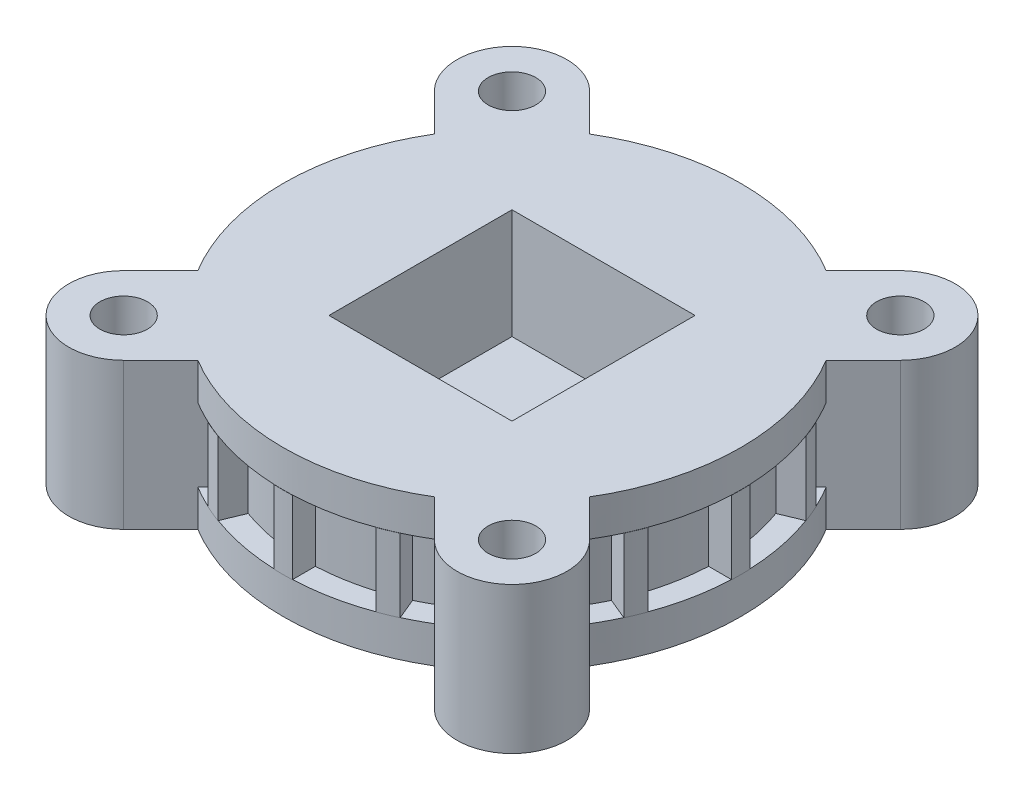
SolidWorks part; units mm, degrees
ref_plane "Front Plane" through (0, 0, 0) normal (0, 0, 1) x (1, 0, 0)
ref_plane "Top Plane" through (0, 0, 0) normal (0, 1, 0) x (1, 0, 0)
ref_plane "Right Plane" through (0, 0, 0) normal (1, 0, 0) x (0, 0, -1)
sketch "Sketch1" plane through (0, 0, 0) normal (0, 1, 0) x (1, 0, 0)
  line L1 (21.4036, 12.9184) -> (25.4558, 16.9706)
  line L2 (12.9184, 21.4036) -> (16.9706, 25.4558)
  line L6 (21.4036, -12.9184) -> (25.4558, -16.9706)
  line L7 (12.9184, -21.4036) -> (16.9706, -25.4558)
  line L8 (-12.9184, -21.4036) -> (-16.9706, -25.4558)
  line L9 (-21.4036, -12.9184) -> (-25.4558, -16.9706)
  line L10 (-21.4036, 12.9184) -> (-25.4558, 16.9706)
  line L11 (-12.9184, 21.4036) -> (-16.9706, 25.4558)
  arc A0 (-12.9184, -21.4036) -> (12.9184, -21.4036) centre (0, 0) ccw
  arc A2 (16.9706, -25.4558) -> (25.4558, -16.9706) centre (21.2132, -21.2132) ccw
  arc A3 (-25.4558, -16.9706) -> (-16.9706, -25.4558) centre (-21.2132, -21.2132) ccw
  arc A4 (-16.9706, 25.4558) -> (-25.4558, 16.9706) centre (-21.2132, 21.2132) ccw
  arc A5 (21.4036, -12.9184) -> (21.4036, 12.9184) centre (0, 0) ccw
  arc A6 (12.9184, 21.4036) -> (-12.9184, 21.4036) centre (0, 0) ccw
  arc A7 (25.4558, 16.9706) -> (16.9706, 25.4558) centre (21.2132, 21.2132) ccw
  arc A8 (-21.4036, 12.9184) -> (-21.4036, -12.9184) centre (0, 0) ccw
  point P14 (0, 0)
  point P35 (0, 0)
  dimension "D1" = 4
extrude "Boss-Extrude1" add sketch "Sketch1" along normal blind 4
ref_plane "Plane1" through (0, 4, 0) normal (0, 1, 0) x (1, 0, 0)
sketch "Sketch2" plane through (0, 4, 0) normal (0, 1, 0) x (1, 0, 0)
  line L0 (-1, 25) -> (-1, 22.4778)
  line L1 (19.5764, 11.0911) -> (25.4558, 16.9706)
  line L2 (11.0911, 19.5764) -> (16.9706, 25.4558)
  line L3 (8.6432, 23.4797) -> (7.678, 21.1494)
  line L4 (1, 25) -> (1, 22.4778)
  line L5 (10.491, 22.7143) -> (9.5257, 20.3841)
  line L6 (19.5764, -11.0911) -> (25.4558, -16.9706)
  line L7 (11.0911, -19.5764) -> (16.9706, -25.4558)
  line L8 (22.7143, 10.491) -> (20.3841, 9.5257)
  line L9 (23.4797, 8.6432) -> (21.1494, 7.678)
  line L10 (25, 1) -> (22.4778, 1)
  line L11 (25, -1) -> (22.4778, -1)
  line L12 (23.4797, -8.6432) -> (21.1494, -7.678)
  line L13 (22.7143, -10.491) -> (20.3841, -9.5257)
  line L16 (10.491, -22.7143) -> (9.5257, -20.3841)
  line L17 (8.6432, -23.4797) -> (7.678, -21.1494)
  line L18 (1, -25) -> (1, -22.4778)
  line L19 (-1, -25) -> (-1, -22.4778)
  line L20 (-8.6432, -23.4797) -> (-7.678, -21.1494)
  line L21 (-10.491, -22.7143) -> (-9.5257, -20.3841)
  line L22 (-11.0911, -19.5764) -> (-16.9706, -25.4558)
  line L23 (-19.5764, -11.0911) -> (-25.4558, -16.9706)
  line L24 (-22.7143, -10.491) -> (-20.3841, -9.5257)
  line L25 (-23.4797, -8.6432) -> (-21.1494, -7.678)
  line L26 (-25, -1) -> (-22.4778, -1)
  line L27 (-25, 1) -> (-22.4778, 1)
  line L28 (-23.4797, 8.6432) -> (-21.1494, 7.678)
  line L29 (-22.7143, 10.491) -> (-20.3841, 9.5257)
  line L30 (-19.5764, 11.0911) -> (-25.4558, 16.9706)
  line L31 (-11.0911, 19.5764) -> (-16.9706, 25.4558)
  line L32 (-10.491, 22.7143) -> (-9.5257, 20.3841)
  line L33 (-8.6432, 23.4797) -> (-7.678, 21.1494)
  line L34 (18.3848, 16.9706) -> (14.8881, 13.4739) [skipped]
  line L35 (16.9706, 18.3848) -> (13.4739, 14.8881) [skipped]
  line L36 (-16.9706, 18.3848) -> (-15.1871, 16.6013) [skipped]
  line L37 (-18.3848, 16.9706) -> (-16.6013, 15.1871) [skipped]
  line L38 (-16.6013, -15.1871) -> (-14.8881, -13.4739) [skipped]
  line L39 (-16.9706, -18.3848) -> (-15.1871, -16.6013) [skipped]
  line L40 (16.9706, -18.3848) -> (15.1871, -16.6013) [skipped]
  line L41 (18.3848, -16.9706) -> (16.6013, -15.1871) [skipped]
  arc A0 (11.0911, 19.5764) -> (9.5257, 20.3841) centre (0, 0) ccw
  arc A1 (25.4558, 16.9706) -> (16.9706, 25.4558) centre (21.2132, 21.2132) ccw
  arc A2 (-22.7143, 10.491) -> (-23.4797, 8.6432) centre (0, 0) ccw
  arc A3 (-11.0911, -19.5764) -> (-9.5257, -20.3841) centre (0, 0) ccw
  arc A4 (16.9706, -25.4558) -> (25.4558, -16.9706) centre (21.2132, -21.2132) ccw
  arc A5 (-25.4558, -16.9706) -> (-16.9706, -25.4558) centre (-21.2132, -21.2132) ccw
  arc A6 (-16.9706, 25.4558) -> (-25.4558, 16.9706) centre (-21.2132, 21.2132) ccw
  arc A7 (-19.5764, 11.0911) -> (-20.3841, 9.5257) centre (0, 0) ccw
  arc A8 (-10.491, -22.7143) -> (-8.6432, -23.4797) centre (0, 0) ccw
  arc A9 (8.6432, -23.4797) -> (10.491, -22.7143) centre (0, 0) ccw
  arc A10 (-1, -25) -> (1, -25) centre (0, 0) ccw
  arc A11 (22.7143, -10.491) -> (23.4797, -8.6432) centre (0, 0) ccw
  arc A12 (19.5764, -11.0911) -> (20.3841, -9.5257) centre (0, 0) ccw
  arc A13 (-7.678, -21.1494) -> (-1, -22.4778) centre (0, 0) ccw
  arc A14 (1, -22.4778) -> (7.678, -21.1494) centre (0, 0) ccw
  arc A15 (9.5257, -20.3841) -> (11.0911, -19.5764) centre (0, 0) ccw
  arc A16 (25, -1) -> (25, 1) centre (0, 0) ccw
  arc A17 (7.678, 21.1494) -> (1, 22.4778) centre (0, 0) ccw
  arc A18 (23.4797, 8.6432) -> (22.7143, 10.491) centre (0, 0) ccw
  arc A19 (20.3841, 9.5257) -> (19.5764, 11.0911) centre (0, 0) ccw
  arc A20 (22.4778, 1) -> (21.1494, 7.678) centre (0, 0) ccw
  arc A21 (21.1494, -7.678) -> (22.4778, -1) centre (0, 0) ccw
  arc A22 (-23.4797, -8.6432) -> (-22.7143, -10.491) centre (0, 0) ccw
  arc A23 (-25, 1) -> (-25, -1) centre (0, 0) ccw
  arc A24 (-21.1494, 7.678) -> (-22.4778, 1) centre (0, 0) ccw
  arc A25 (-22.4778, -1) -> (-21.1494, -7.678) centre (0, 0) ccw
  arc A26 (-20.3841, -9.5257) -> (-19.5764, -11.0911) centre (0, 0) ccw
  arc A27 (-8.6432, 23.4797) -> (-10.491, 22.7143) centre (0, 0) ccw
  arc A28 (1, 25) -> (-1, 25) centre (0, 0) ccw
  arc A29 (10.491, 22.7143) -> (8.6432, 23.4797) centre (0, 0) ccw
  arc A30 (-1, 22.4778) -> (-7.678, 21.1494) centre (0, 0) ccw
  arc A31 (-9.5257, 20.3841) -> (-11.0911, 19.5764) centre (0, 0) ccw
  point P75 (0, 0)
  point P95 (0, 0)
  dimension "D1" = 16
  dimension "D2" = 4
extrude "Boss-Extrude2" add sketch "Sketch2" along normal blind 8
ref_plane "Plane2" through (0, 12, 0) normal (0, 1, 0) x (1, 0, 0)
sketch "Sketch3" plane through (0, 12, 0) normal (0, 1, 0) x (1, 0, 0)
  line L0 (21.4036, -12.9184) -> (25.4558, -16.9706)
  line L1 (21.4036, 12.9184) -> (25.4558, 16.9706)
  line L2 (12.9184, 21.4036) -> (16.9706, 25.4558)
  line L3 (12.9184, -21.4036) -> (16.9706, -25.4558)
  line L4 (-12.9184, -21.4036) -> (-16.9706, -25.4558)
  line L5 (-21.4036, -12.9184) -> (-25.4558, -16.9706)
  line L6 (-21.4036, 12.9184) -> (-25.4558, 16.9706)
  line L7 (-12.9184, 21.4036) -> (-16.9706, 25.4558)
  arc A0 (12.9184, 21.4036) -> (-12.9184, 21.4036) centre (0, 0) ccw
  arc A1 (25.4558, 16.9706) -> (16.9706, 25.4558) centre (21.2132, 21.2132) ccw
  arc A2 (16.9706, -25.4558) -> (25.4558, -16.9706) centre (21.2132, -21.2132) ccw
  arc A3 (-25.4558, -16.9706) -> (-16.9706, -25.4558) centre (-21.2132, -21.2132) ccw
  arc A4 (-16.9706, 25.4558) -> (-25.4558, 16.9706) centre (-21.2132, 21.2132) ccw
  arc A5 (-12.9184, -21.4036) -> (12.9184, -21.4036) centre (0, 0) ccw
  arc A6 (-21.4036, 12.9184) -> (-21.4036, -12.9184) centre (0, 0) ccw
  arc A7 (21.4036, -12.9184) -> (21.4036, 12.9184) centre (0, 0) ccw
  point P27 (0, 0)
  dimension "D1" = 4
extrude "Boss-Extrude3" add sketch "Sketch3" along normal blind 4
ref_plane "Plane3" through (0, 16, 0) normal (0, 1, 0) x (1, 0, 0)
sketch "Sketch4" plane through (0, 16, 0) normal (0, 1, 0) x (1, 0, 0)
  circle A0 centre (-21.2132, -21.2132) radius 2.6
  circle A1 centre (-21.2132, 21.2132) radius 2.6
  circle A2 centre (21.2132, 21.2132) radius 2.6
  circle A3 centre (21.2132, -21.2132) radius 2.6
  point P13 (0, 0)
  dimension "D1" = 4
extrude "Cut-Extrude1" cut sketch "Sketch4" against normal blind 12
sketch "Sketch5" plane through (0, 16, 0) normal (0, 1, 0) x (1, 0, 0)
  line L1 (-10, -10) -> (10, -10)
  line L2 (-10, -10) -> (-10, 10)
  line L3 (-10, 10) -> (10, 10)
  line L4 (10, -10) -> (10, 10)
  line L5 (-10, -10) -> (10, 10) construction
  line L6 (-10, 10) -> (10, -10) construction
  point P0 (0, 0)
extrude "Cut-Extrude2" cut sketch "Sketch5" against normal blind 12
